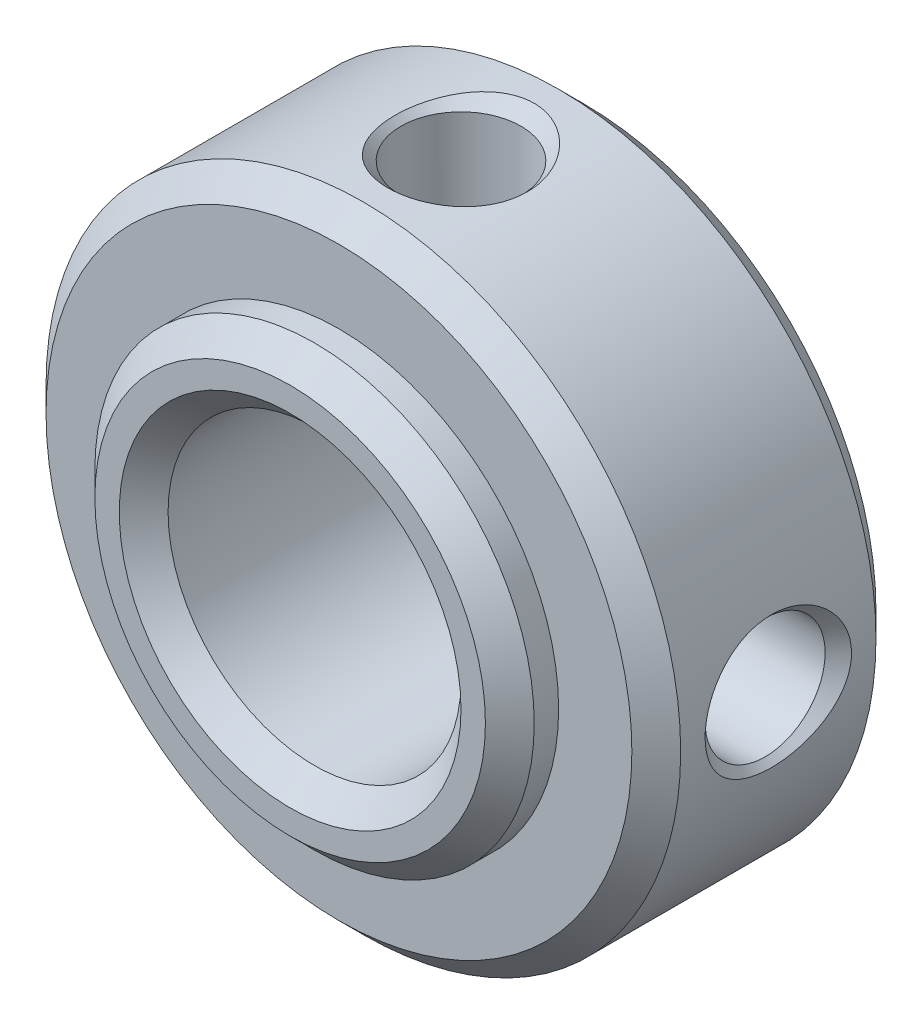
SolidWorks part; units mm, degrees
ref_plane "Plan de face" through (0, 0, 0) normal (0, 0, 1) x (1, 0, 0)
ref_plane "Plan de dessus" through (0, 0, 0) normal (0, 1, 0) x (1, 0, 0)
ref_plane "Plan de droite" through (0, 0, 0) normal (1, 0, 0) x (0, 0, -1)
ref_plane "Plan1" through (0, 0, 0) normal (0, 1, 0) x (1, 0, 0)
sketch "Esquisse1" plane through (0, 0, 0) normal (0, 1, 0) x (1, 0, 0)
  line L0 (3, 2) -> (3, -3)
  line L1 (3, -3) -> (3.5, -3.5)
  line L2 (3.5, -3.5) -> (4, -3.5)
  line L3 (4, -3.5) -> (4.5, -3)
  line L4 (4.5, -3) -> (4.5, -2.5)
  line L5 (4.5, -2.5) -> (6, -2.5)
  line L6 (6, -2.5) -> (6.5, -2)
  line L7 (6.5, -2) -> (6.5, 2)
  line L8 (6.5, 2) -> (6, 2.5)
  line L9 (6, 2.5) -> (3.5, 2.5)
  line L10 (3.5, 2.5) -> (3, 2)
  line L11 (0, -3.5) -> (0, 2.5) construction
revolve "Révolution1" add sketch "Esquisse1" angle 360 about L11
ref_plane "Plan2" through (0, 0, 0) normal (0, 0, 1) x (1, 0, 0)
sketch "Esquisse2" plane through (0, 0, 0) normal (0, 0, 1) x (1, 0, 0)
  line L0 (2, 0) -> (2, 1.2295)
  line L1 (2, 1.2295) -> (6.2295, 1.2295)
  line L2 (6.2295, 1.2295) -> (6.5, 1.5)
  line L3 (6.5, 1.5) -> (6.5, 0)
  line L4 (6.5, 0) -> (2, 0)
  line L5 (6.5, 0) -> (2, 0) construction
revolve "Enlèvement de matière-Révolution1" cut sketch "Esquisse2" angle 360 about L5
ref_plane "Plan3" through (0, 0, 0) normal (0, 0, 1) x (1, 0, 0)
sketch "Esquisse3" plane through (0, 0, 0) normal (0, 0, 1) x (1, 0, 0)
  line L0 (0, 2) -> (-1.2295, 2)
  line L1 (-1.2295, 2) -> (-1.2295, 6.2295)
  line L2 (-1.2295, 6.2295) -> (-1.5, 6.5)
  line L3 (-1.5, 6.5) -> (0, 6.5)
  line L4 (0, 6.5) -> (0, 2)
  line L5 (0, 6.5) -> (0, 2) construction
revolve "Enlèvement de matière-Révolution2" cut sketch "Esquisse3" angle 360 about L5
